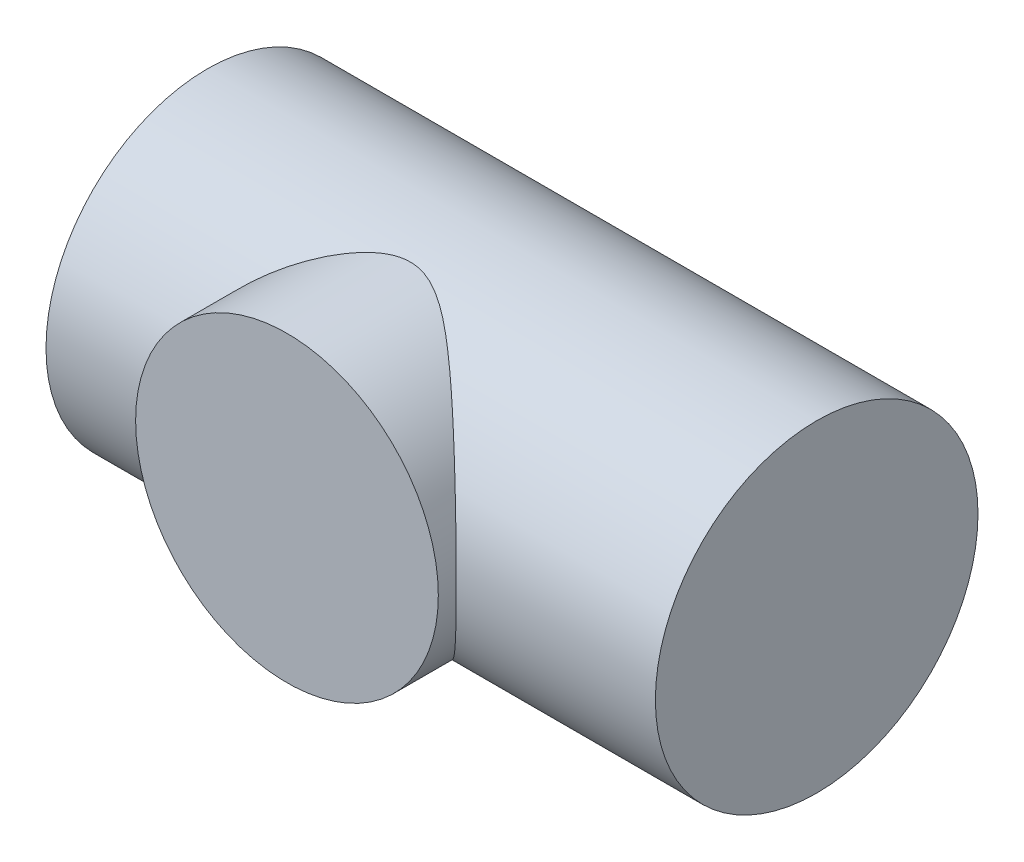
SolidWorks part; units mm, degrees
ref_plane "Front Plane" through (0, 0, 0) normal (0, 0, 1) x (1, 0, 0)
ref_plane "Top Plane" through (0, 0, 0) normal (0, 1, 0) x (1, 0, 0)
ref_plane "Right Plane" through (0, 0, 0) normal (1, 0, 0) x (0, 0, -1)
other "Graphic1"
sketch "Sketch1" plane through (0, 0, 0) normal (1, 0, 0) x (0, 0, -1)
  circle A0 centre (0, 0) radius 0.0405
extrude "Boss-Extrude1" add sketch "Sketch1" along normal blind 0.153 from offset 0.065 offset against normal yes
sketch "Sketch2" plane through (0, 0, 0) normal (0, 0, 1) x (1, 0, 0)
  circle A0 centre (0, 0) radius 0.038
extrude "Boss-Extrude2" add sketch "Sketch2" along normal blind 0.045
